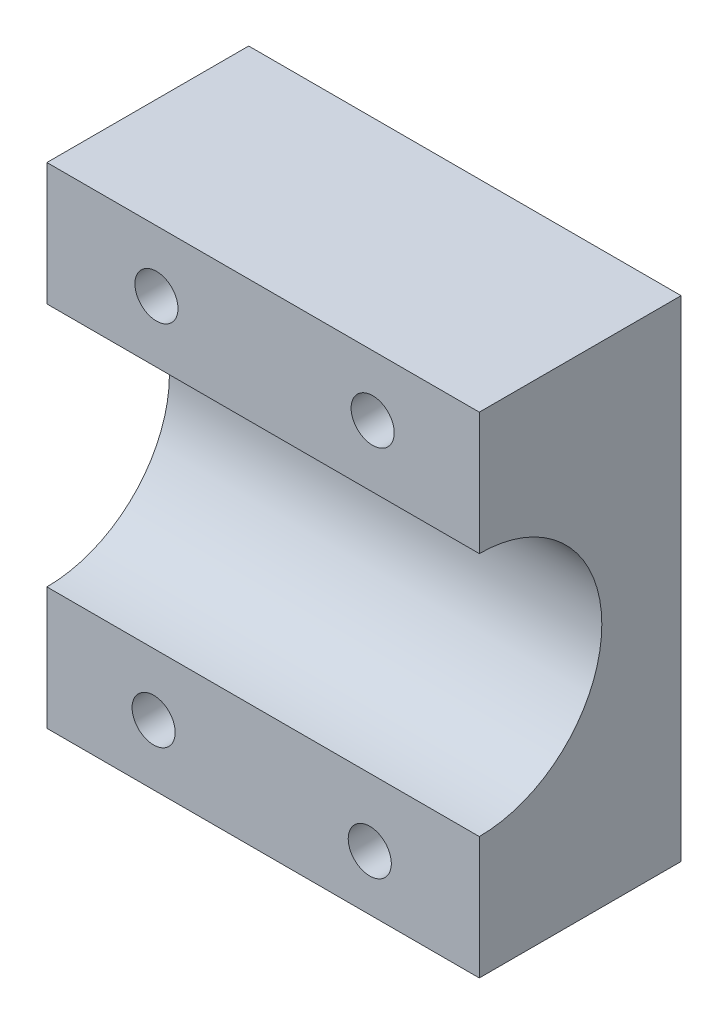
SolidWorks part; units mm, degrees
ref_plane "Front Plane" through (0, 0, 0) normal (0, 0, 1) x (1, 0, 0)
ref_plane "Top Plane" through (0, 0, 0) normal (0, 1, 0) x (1, 0, 0)
ref_plane "Right Plane" through (0, 0, 0) normal (1, 0, 0) x (0, 0, -1)
sketch "Sketch1" plane through (0, 0, 0) normal (0, 0, 1) x (1, 0, 0)
  line L1 (0, 0) -> (38.1, 0)
  line L2 (0, 0) -> (0, 43.18)
  line L3 (0, 43.18) -> (38.1, 43.18)
  line L4 (38.1, 0) -> (38.1, 43.18)
  dimension "D1" = 38.1
  dimension "D2" = 43.18
extrude "Boss-Extrude1" add sketch "Sketch1" along normal blind 17.78
sketch "Sketch2" plane through (0, 0, 0) normal (-1, 0, 0) x (0, 0, 1)
  line L0 (17.78, 43.18) -> (17.78, 0) construction
  circle A0 centre (17.78, 21.59) radius 10.795
  dimension "D1" = 21.59
extrude "Cut-Extrude1" cut sketch "Sketch2" against normal through all
hole_wizard "CBORE for #6 Binding Head Machine Screw1" positions "3DSketch1" profile "Sketch3" counterbore size "#6" standard "ANSI Inch" end condition through all
sketch3d "3DSketch1"
  line L0 (38.1, 43.18, 0) -> (0, 43.18, 0) construction
  line L1 (0, 43.18, 0) -> (0, 0, 0) construction
  line L2 (38.1, 0, 0) -> (38.1, 43.18, 0) construction
  line L3 (0, 0, 0) -> (38.1, 0, 0) construction
  point P0 (28.702, 37.846, 0)
  point P2 (9.652, 37.8052, 0)
  point P4 (28.448, 4.8551, 0)
  point P6 (9.404, 5.334, 0)
  point P7 (0, 0, 0)
  dimension "D1" = 19.05
  dimension "D2" = 19.05
  dimension "D3" = 5.334
  dimension "D4" = 9.652
  dimension "D5" = 9.652
  dimension "D6" = 5.334
sketch "Sketch3" plane through (28.702, 37.846, 0) normal (1, 0, 0) x (0, 1, 0)
  line L0 (0, 0) -> (0, 17.78)
  line L1 (0, 17.78) -> (1.8986, 17.78)
  line L3 (1.8986, 17.78) -> (1.8987, 2.2098)
  line L4 (1.8987, 2.2098) -> (3.9687, 2.2098)
  line L5 (3.9687, 2.2098) -> (3.9687, 0)
  line L7 (3.9687, 0) -> (0, 0)
  line L11 (0, -6.35) -> (0, 107.95) construction
  dimension "Thru Hole Dia." = 3.7973
  dimension "Thru Hole Depth" = 17.78
  dimension "C'Bore Dia." = 7.9375
  dimension "C'Bore Depth" = 2.2098
